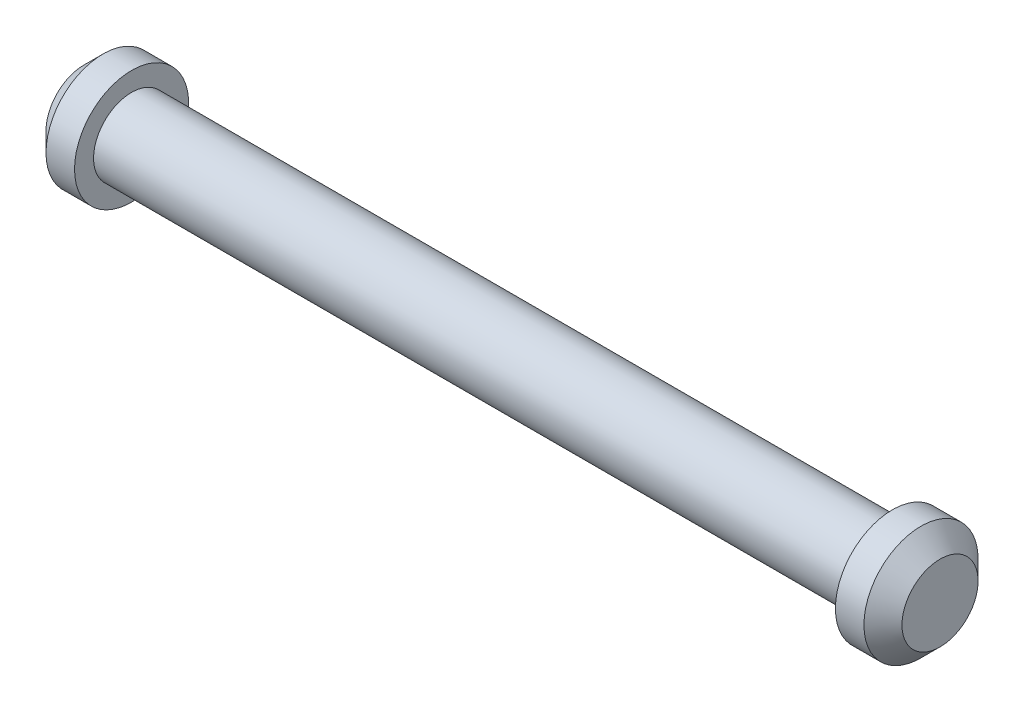
SolidWorks part; units mm, degrees
ref_plane "Front Plane" through (0, 0, 0) normal (0, 0, 1) x (1, 0, 0)
ref_plane "Top Plane" through (0, 0, 0) normal (0, 1, 0) x (1, 0, 0)
ref_plane "Right Plane" through (0, 0, 0) normal (1, 0, 0) x (0, 0, -1)
sketch "Sketch1" plane through (0, 0, 0) normal (0, 0, 1) x (1, 0, 0)
  line L0 (0, 0) -> (19993.5358, 0) construction
  line L1 (0, 0) -> (0, -19993.5358) construction
  line L2 (-45, 0) -> (-45, 4)
  line L3 (-43, 6) -> (-40, 6)
  line L4 (-40, 6) -> (-40, 4)
  line L5 (-40, 4) -> (40, 4)
  line L6 (40, 6) -> (40, 4)
  line L7 (43, 6) -> (40, 6)
  line L8 (45, 0) -> (45, 4)
  line L9 (-45, 4) -> (-43, 6)
  line L10 (45, 4) -> (43, 6)
  line L11 (-45, 0) -> (45, 0)
  point P6 (-45, 6)
  point P7 (45, 6)
  point P12 (0, 4)
  dimension "D1" = 5
  dimension "D2" = 80
  dimension "D3" = 12
  dimension "D4" = 8
  dimension "D5" = 2
  dimension "D6" = 45
  dimension "D7" = 2
  dimension "D8" = 45
revolve "Revolve1" add sketch "Sketch1" angle 360 about L11
